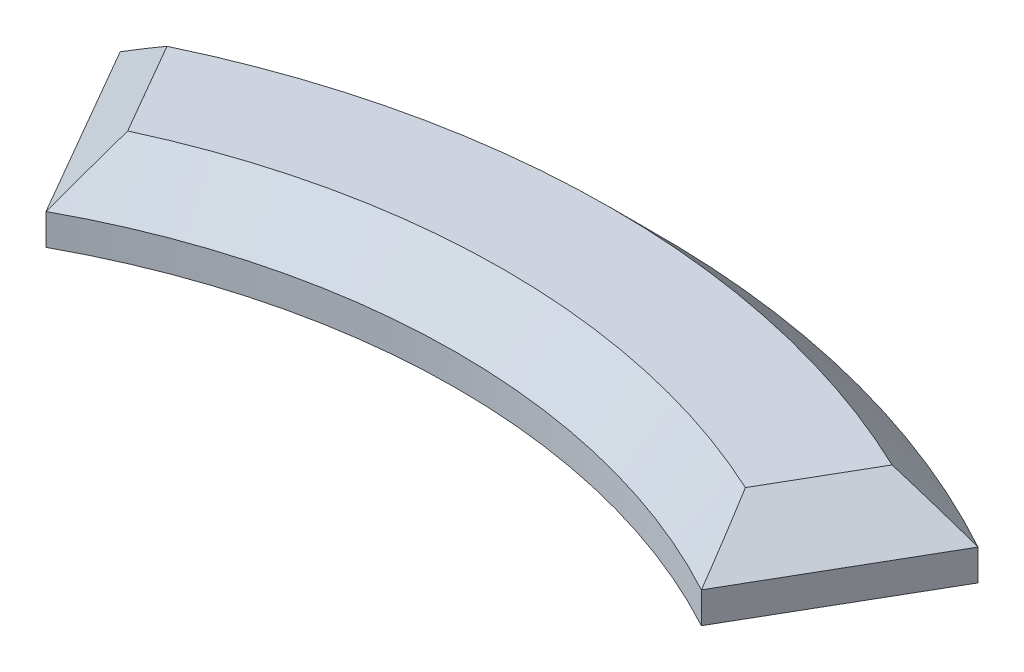
SolidWorks part; units mm, degrees
ref_plane "Front Plane" through (0, 0, 0) normal (0, 0, 1) x (1, 0, 0)
ref_plane "Top Plane" through (0, 0, 0) normal (0, 1, 0) x (1, 0, 0)
ref_plane "Right Plane" through (0, 0, 0) normal (1, 0, 0) x (0, 0, -1)
sketch "Sketch1" plane through (0, 0, 0) normal (0, 1, 0) x (1, 0, 0)
  line L0 (-14, 24.2487) -> (-19, 32.909) construction
  line L1 (14, 24.2487) -> (19, 32.909) construction
  line L2 (0, 0) -> (4, 0) construction
  line L3 (-17.9717, 32.6279) -> (-13.7293, 25.2798)
  line L4 (17.9717, 32.6279) -> (13.7293, 25.2798)
  line L5 (-16.5, 28.5788) -> (-15.8505, 28.9538) construction
  line L6 (15.8505, 28.9538) -> (16.5, 28.5788) construction
  circle A0 centre (0, 0) radius 28 construction
  circle A1 centre (0, 0) radius 38 construction
  arc A2 (-17.9717, 32.6279) -> (17.9717, 32.6279) centre (0, 0) cw
  arc A3 (-13.7293, 25.2798) -> (13.7293, 25.2798) centre (0, 0) cw
  point P19 (16.5, 28.5788)
  dimension "D1" = 28
  dimension "D2" = 38
  dimension "D4" = 0.75
  dimension "D6" = 60
  dimension "D3" = 60
  dimension "D5" = 0.75
extrude "Boss-Extrude1" add sketch "Sketch1" along normal blind 3.3
chamfer "Chamfer1" distance 2 angle 45 4 edges at (15.8505, 3.3, -28.9538) (0, 3.3, -37.25) (0, 3.3, -28.7673) (-15.8505, 3.3, -28.9538)
sketch "Sketch2" plane through (0, 0, 0) normal (0, -1, 0) x (1, 0, 0)
  line L0 (0, -37.25) -> (0, -28.7673) construction
  arc A0 (-17.9717, -32.6279) -> (17.9717, -32.6279) centre (0, 0) ccw construction
  arc A1 (-13.7293, -25.2798) -> (13.7293, -25.2798) centre (0, 0) ccw construction
  circle A2 centre (0, -33.0087) radius 1.625
  dimension "D1" = 3.25
extrude "Cut-Extrude1" cut sketch "Sketch2" against normal blind 2
